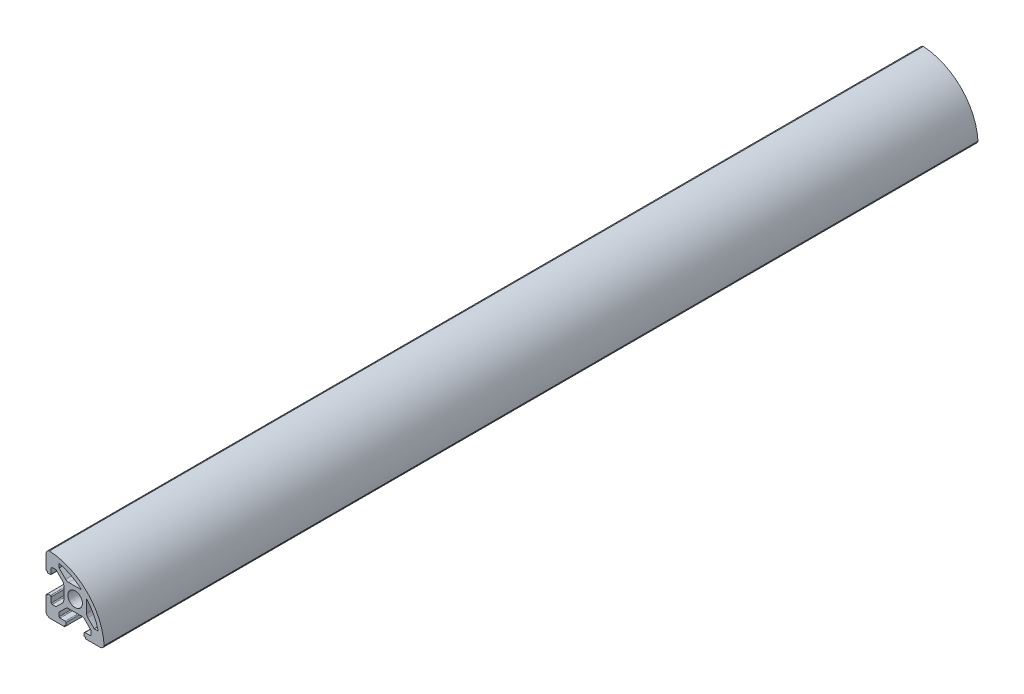
SolidWorks part; units mm, degrees
ref_plane "前视基准面" through (0, 0, 0) normal (0, 0, 1) x (1, 0, 0)
ref_plane "上视基准面" through (0, 0, 0) normal (0, 1, 0) x (1, 0, 0)
ref_plane "右视基准面" through (0, 0, 0) normal (1, 0, 0) x (0, 0, -1)
sketch "草图1" plane through (0, 0, 0) normal (0, 0, 1) x (1, 0, 0)
  line L14 (2.0848, 3.8649) -> (-2.342, 3.8649)
  line L15 (-3.4027, 4.3042) -> (-5.6233, 6.5249)
  line L16 (-5.6233, 6.5249) -> (-5.6233, 7.8649)
  line L22 (-10.1233, 8.4649) -> (-10.1233, 3.5649)
  line L23 (-10.1233, 3.5649) -> (-9.8233, 3.5649)
  line L24 (-9.6233, 3.3649) -> (-9.6233, 3.0649)
  line L25 (-9.6233, 3.0649) -> (-8.6233, 3.0649)
  line L26 (-8.3233, 3.3649) -> (-8.3233, 5.1649)
  line L27 (-8.0233, 5.4649) -> (-6.6833, 5.4649)
  line L28 (-6.6833, 5.4649) -> (-4.4627, 3.2442)
  line L29 (-4.0233, 2.1836) -> (-4.0233, -2.2538)
  line L30 (-4.4627, -3.3144) -> (-6.6833, -5.5351)
  line L31 (-6.6833, -5.5351) -> (-8.0233, -5.5351)
  line L32 (-8.3233, -5.2351) -> (-8.3233, -3.4351)
  line L33 (-8.6233, -3.1351) -> (-9.6233, -3.1351)
  line L34 (-9.6233, -3.1351) -> (-9.6233, -3.4351)
  line L35 (-9.8233, -3.6351) -> (-10.1233, -3.6351)
  line L36 (-10.1233, -3.6351) -> (-10.1233, -8.5351)
  line L37 (-8.6233, -10.0351) -> (-3.7233, -10.0351)
  line L38 (-3.7233, -10.0351) -> (-3.7233, -9.7351)
  line L39 (-3.5233, -9.5351) -> (-3.2233, -9.5351)
  line L40 (-3.2233, -9.5351) -> (-3.2233, -8.5351)
  line L41 (-3.5233, -8.2351) -> (-5.3233, -8.2351)
  line L42 (-5.6233, -7.9351) -> (-5.6233, -6.5951)
  line L43 (-5.6233, -6.5951) -> (-3.4027, -4.3744)
  line L44 (-2.342, -3.9351) -> (2.0953, -3.9351)
  line L45 (3.156, -4.3744) -> (5.3767, -6.5951)
  line L46 (5.3767, -6.5951) -> (5.3767, -7.9351)
  line L47 (5.0767, -8.2351) -> (3.2767, -8.2351)
  line L48 (2.9767, -8.5351) -> (2.9767, -9.5351)
  line L49 (2.9767, -9.5351) -> (3.2767, -9.5351)
  line L50 (3.4767, -9.7351) -> (3.4767, -10.0351)
  line L51 (3.4767, -10.0351) -> (8.3767, -10.0351)
  line L57 (7.7767, -5.5351) -> (6.4367, -5.5351)
  line L58 (6.4367, -5.5351) -> (4.216, -3.3144)
  line L59 (3.7767, -2.2538) -> (3.7767, 2.1836)
  circle A0 centre (-0.1233, -0.0351) radius 2.5
  arc A1 (7.8202, -5.5319) -> (3.7767, 2.1731) centre (-10.1233, -10.0351) ccw
  arc A2 (2.0848, 3.8649) -> (-5.6202, 7.9085) centre (-10.1233, -10.0351) ccw
  arc A9 (-3.4027, 4.3042) -> (-2.342, 3.8649) centre (-2.342, 5.3649) ccw
  arc A10 (-5.3233, 8.1649) -> (-5.6233, 7.8649) centre (-5.3233, 7.8649) ccw
  arc A13 (-8.6233, 9.9649) -> (-10.1233, 8.4649) centre (-8.6233, 8.4649) ccw
  arc A14 (-9.6233, 3.3649) -> (-9.8233, 3.5649) centre (-9.8233, 3.3649) ccw
  arc A15 (-8.6233, 3.0649) -> (-8.3233, 3.3649) centre (-8.6233, 3.3649) ccw
  arc A16 (-8.0233, 5.4649) -> (-8.3233, 5.1649) centre (-8.0233, 5.1649) ccw
  arc A17 (-4.0233, 2.1836) -> (-4.4627, 3.2442) centre (-5.5233, 2.1836) ccw
  arc A18 (-4.4627, -3.3144) -> (-4.0233, -2.2538) centre (-5.5233, -2.2538) ccw
  arc A19 (-8.3233, -5.2351) -> (-8.0233, -5.5351) centre (-8.0233, -5.2351) ccw
  arc A20 (-8.3233, -3.4351) -> (-8.6233, -3.1351) centre (-8.6233, -3.4351) ccw
  arc A21 (-9.8233, -3.6351) -> (-9.6233, -3.4351) centre (-9.8233, -3.4351) ccw
  arc A22 (-10.1233, -8.5351) -> (-8.6233, -10.0351) centre (-8.6233, -8.5351) ccw
  arc A23 (-3.5233, -9.5351) -> (-3.7233, -9.7351) centre (-3.5233, -9.7351) ccw
  arc A24 (-3.2233, -8.5351) -> (-3.5233, -8.2351) centre (-3.5233, -8.5351) ccw
  arc A25 (-5.6233, -7.9351) -> (-5.3233, -8.2351) centre (-5.3233, -7.9351) ccw
  arc A26 (-2.342, -3.9351) -> (-3.4027, -4.3744) centre (-2.342, -5.4351) ccw
  arc A27 (3.156, -4.3744) -> (2.0953, -3.9351) centre (2.0953, -5.4351) ccw
  arc A28 (5.0767, -8.2351) -> (5.3767, -7.9351) centre (5.0767, -7.9351) ccw
  arc A29 (3.2767, -8.2351) -> (2.9767, -8.5351) centre (3.2767, -8.5351) ccw
  arc A30 (3.4767, -9.7351) -> (3.2767, -9.5351) centre (3.2767, -9.7351) ccw
  arc A31 (8.3767, -10.0351) -> (9.8767, -8.5351) centre (8.3767, -8.5351) ccw
  arc A34 (7.7767, -5.5351) -> (7.8202, -5.5319) centre (7.7767, -5.2351) ccw
  arc A35 (3.7767, -2.2538) -> (4.216, -3.3144) centre (5.2767, -2.2538) ccw
  arc A37 (9.8419, -8.8562) -> (-8.9445, 9.9301) centre (-10.1233, -10.0351) ccw
extrude "凸台-拉伸1" add sketch "草图1" along normal blind 300 contours A31 A37 A13 L22 L23 A14 L24 L25 A15 L26 A16 L27 L28 A17 L29 A18 L30 L31 A19 L32 A20 L33 L34 A21 L35 L36 A22 L37 L38 A23 L39 L40 A24 L41 A25 L42 L43 A26 L44 A27 L45 L46 A28 L47 A29 L48 L49 A30 L50 L51
